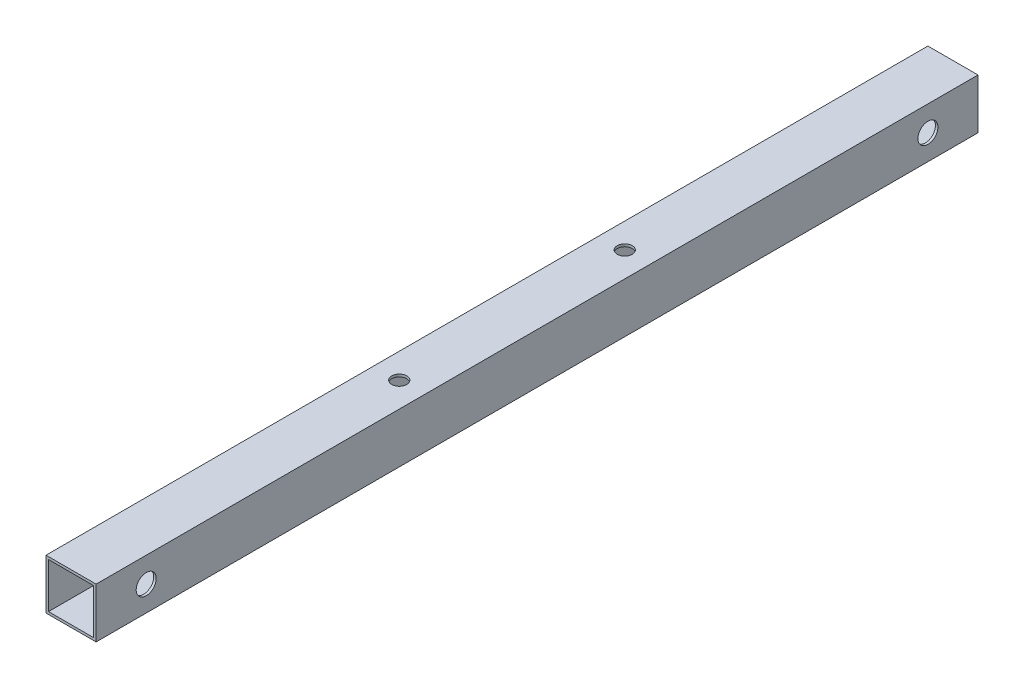
SolidWorks part; units mm, degrees
ref_plane "前视基准面" through (0, 0, 0) normal (0, 0, 1) x (1, 0, 0)
ref_plane "上视基准面" through (0, 0, 0) normal (0, 1, 0) x (1, 0, 0)
ref_plane "右视基准面" through (0, 0, 0) normal (1, 0, 0) x (0, 0, -1)
sketch "草图1" plane through (0, 0, 0) normal (0, 0, 1) x (1, 0, 0)
  line L1 (-5, 5) -> (5, 5)
  line L2 (-5, 5) -> (-5, -5)
  line L3 (-5, -5) -> (5, -5)
  line L4 (5, 5) -> (5, -5)
  line L5 (-5, 5) -> (5, -5) construction
  line L6 (-5, -5) -> (5, 5) construction
  line L7 (-4.5, 4.5) -> (4.5, 4.5)
  line L8 (-4.5, 4.5) -> (-4.5, -4.5)
  line L9 (-4.5, -4.5) -> (4.5, -4.5)
  line L10 (4.5, 4.5) -> (4.5, -4.5)
  line L11 (-4.5, 4.5) -> (4.5, -4.5) construction
  line L12 (-4.5, -4.5) -> (4.5, 4.5) construction
  point P0 (0, 0)
  point P5 (0, 0)
  dimension "D1" = 10
  dimension "D2" = 10
extrude "凸台-拉伸1" add sketch "草图1" along normal blind 176
sketch "草图2" plane through (-5, 0, 0) normal (-1, 0, 0) x (0, 0, 1)
  line L0 (5.5, 0) -> (-5.5, 0) construction
  line L1 (0, -5.5) -> (0, 5.5) construction
  line L2 (176, 5) -> (176, -5) construction
  circle A0 centre (10, 0) radius 2
  circle A1 centre (166, 0) radius 2
  dimension "D1" = 10
  dimension "D2" = 10
extrude "切除-拉伸1" cut sketch "草图2" against normal blind 176
sketch "草图3" plane through (0, 5, 0) normal (0, 1, 0) x (1, 0, 0)
  line L0 (0, -5.5) -> (0, 5.5) construction
  line L1 (5, -176) -> (-5, -176) construction
  circle A0 centre (0, -65.5) radius 1.5
  circle A1 centre (0, -110.5) radius 1.5
  dimension "D1" = 65.5
  dimension "D2" = 65.5
  dimension "D3" = 3
  dimension "D4" = 3
extrude "切除-拉伸2" cut sketch "草图3" against normal blind 176
